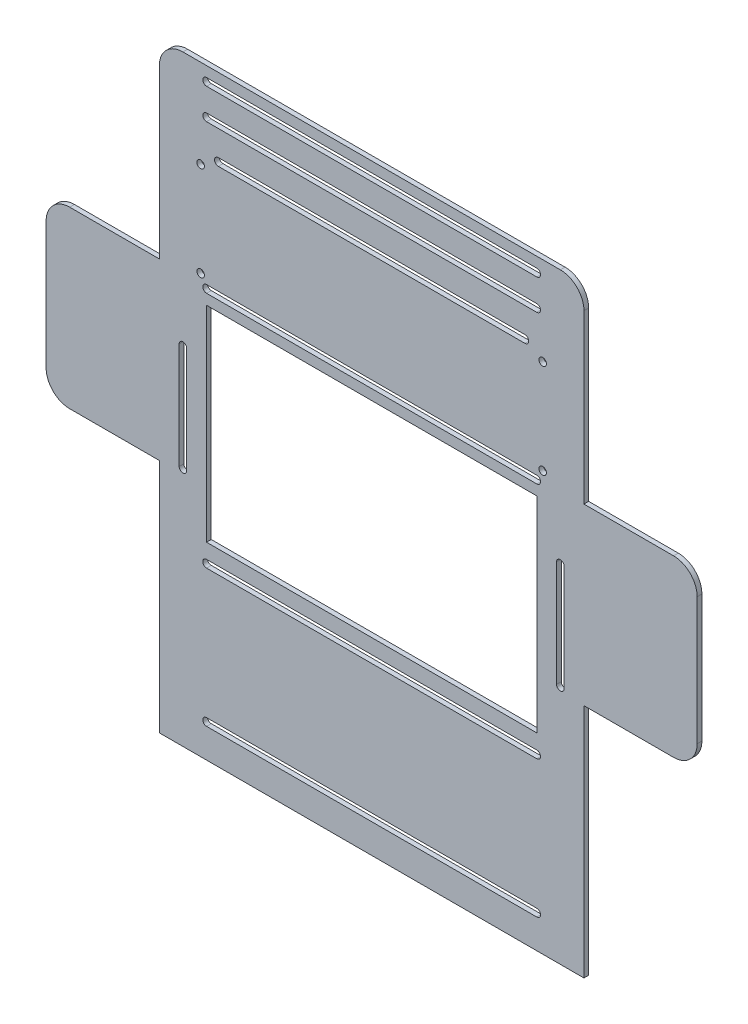
SolidWorks part; units mm, degrees
ref_plane "前视基准面" through (0, 0, 0) normal (0, 0, 1) x (1, 0, 0)
ref_plane "上视基准面" through (0, 0, 0) normal (0, 1, 0) x (1, 0, 0)
ref_plane "右视基准面" through (0, 0, 0) normal (1, 0, 0) x (0, 0, -1)
other "Configuration Table"
sketch "草图2" plane through (0, 0, 0) normal (0, 0, 1) x (1, 0, 0)
  line L0 (90, 100) -> (90, 39)
  line L1 (-90, 100) -> (90, 100)
  line L2 (-90, 100) -> (-90, 39)
  line L3 (-90, -100) -> (90, -100)
  line L5 (0, -100) -> (0, 100) construction
  line L7 (-90, 39) -> (-138, 39)
  line L9 (-90, -35) -> (-138, -35)
  line L10 (-138, 39) -> (-138, -35)
  line L15 (90, -35) -> (138, -35)
  line L16 (138, 39) -> (138, -35)
  line L17 (90, 39) -> (138, 39)
  line L18 (-90, -35) -> (-90, -100)
  line L19 (90, -35) -> (90, -100)
  point P0 (0, 0)
  dimension "D1" = 180
  dimension "D2" = 200
  dimension "D3" = 61
  dimension "D4" = 65
  dimension "D5" = 48
extrude "凸台-拉伸1" add sketch "草图2" along normal blind 2
sketch "草图3" plane through (0, 0, 2) normal (0, 0, 1) x (1, 0, 0)
  line L0 (90, -100) -> (90, -35) construction
  line L1 (-90, -100) -> (90, -100)
  line L2 (-90, -100) -> (-90, -135)
  line L3 (-90, -135) -> (90, -135)
  line L4 (90, -100) -> (90, -135)
  dimension "D1" = 35
extrude "凸台-拉伸2" add sketch "草图3" along direction (0, 0, 1) on the side against the normal up to surface (2 mm away)
sketch "草图4" plane through (0, 0, 2) normal (0, 0, 1) x (1, 0, 0)
  line L0 (90, 39) -> (90, 100) construction
  line L1 (-90, 100) -> (90, 100)
  line L2 (-90, 100) -> (-90, 120)
  line L3 (-90, 120) -> (90, 120)
  line L4 (90, 100) -> (90, 120)
  dimension "D1" = 20
extrude "凸台-拉伸3" add sketch "草图4" against normal up to surface (2 mm away) up to face at (0, -4.5, 0)
sketch "草图5" plane through (0, 0, 0) normal (0, 0, -1) x (-1, 0, 0)
  line L0 (-90, 39) -> (-90, 100) construction
  line L1 (-70, 32) -> (70, 32)
  line L2 (-70, 32) -> (-70, -55)
  line L3 (-70, -55) -> (70, -55)
  line L4 (70, 32) -> (70, -55)
  line L5 (90, 100) -> (90, 39) construction
  line L6 (90, 120) -> (-90, 120) construction
  line L7 (90, -135) -> (-90, -135) construction
  dimension "D1" = 20
  dimension "D2" = 20
  dimension "D3" = 88
  dimension "D4" = 80
extrude "切除-拉伸1" cut sketch "草图5" against normal through all
fillet "圆角1" radius 10 1 edges at (138, -35, 1)
fillet "圆角2" radius 10 1 edges at (138, 39, 1)
fillet "圆角3" radius 10 1 edges at (-138, 39, 1)
fillet "圆角4" radius 10 1 edges at (-138, -35, 1)
sketch "草图7" plane through (0, 0, 0) normal (0, 0, -1) x (-1, 0, 0)
  line L0 (-70, 114) -> (70, 114) construction
  line L1 (-70, 115.6) -> (70, 115.6)
  line L2 (-70, 112.4) -> (70, 112.4)
  line L3 (90, 120) -> (-90, 120) construction
  line L4 (-90, 39) -> (-90, 120) construction
  line L5 (90, 120) -> (90, 39) construction
  line L6 (-70, 101) -> (70, 101) construction
  line L7 (-70, 102.6) -> (70, 102.6)
  line L8 (-70, 99.4) -> (70, 99.4)
  line L9 (-70, 38) -> (70, 38) construction
  line L10 (-70, 39.6) -> (70, 39.6)
  line L11 (-70, 36.4) -> (70, 36.4)
  line L12 (70, 32) -> (-70, 32) construction
  arc A0 (-70, 115.6) -> (-70, 112.4) centre (-70, 114) ccw
  arc A1 (70, 112.4) -> (70, 115.6) centre (70, 114) ccw
  arc A2 (-70, 102.6) -> (-70, 99.4) centre (-70, 101) ccw
  arc A3 (70, 99.4) -> (70, 102.6) centre (70, 101) ccw
  arc A4 (-70, 39.6) -> (-70, 36.4) centre (-70, 38) ccw
  arc A5 (70, 36.4) -> (70, 39.6) centre (70, 38) ccw
  point P2 (0, 114)
  point P7 (0, 101)
  point P22 (0, 38)
  dimension "D1" = 6
  dimension "D2" = 3.2
  dimension "D3" = 20
  dimension "D4" = 20
  dimension "D5" = 63
  dimension "D6" = 6
  dimension "D7" = 3.2
  dimension "D8" = 3.2
  dimension "D9" = 20
  dimension "D10" = 20
  dimension "D11" = 20
  dimension "D12" = 20
extrude "切除-拉伸2" cut sketch "草图7" against normal blind 10
fillet "圆角5" radius 10 1 edges at (-90, 120, 1)
fillet "圆角6" radius 10 1 edges at (90, 120, 1)
sketch "草图10" plane through (0, 0, 0) normal (0, 0, -1) x (-1, 0, 0)
  line L0 (-70, -62.9) -> (70, -62.9) construction
  line L1 (-70, -61.3) -> (70, -61.3)
  line L2 (-70, -64.5) -> (70, -64.5)
  line L3 (-70, -121) -> (70, -121) construction
  line L4 (-70, -119.4) -> (70, -119.4)
  line L5 (-70, -122.6) -> (70, -122.6)
  line L6 (-90, -135) -> (90, -135) construction
  line L7 (-90, -135) -> (-90, -35) construction
  line L8 (90, -35) -> (90, -135) construction
  arc A0 (-70, -61.3) -> (-70, -64.5) centre (-70, -62.9) ccw
  arc A1 (70, -64.5) -> (70, -61.3) centre (70, -62.9) ccw
  arc A2 (-70, -119.4) -> (-70, -122.6) centre (-70, -121) ccw
  arc A3 (70, -122.6) -> (70, -119.4) centre (70, -121) ccw
  point P2 (0, -62.9)
  point P7 (0, -121)
  dimension "D5" = 20
  dimension "D1" = 58.1
  dimension "D2" = 14
  dimension "D3" = 3.2
  dimension "D4" = 3.2
  dimension "D6" = 20
  dimension "D7" = 20
  dimension "D8" = 20
extrude "切除-拉伸5" cut sketch "草图10" against normal blind 10
sketch "草图11" plane through (0, 0, 2) normal (0, 0, 1) x (1, 0, 0)
  line L50 (-65, 87.1) -> (65, 87.1) construction
  line L51 (-65, 88.7) -> (65, 88.7)
  line L52 (-65, 85.5) -> (65, 85.5)
  line L53 (-90, 110) -> (-90, 39) construction
  line L54 (90, 39) -> (90, 110) construction
  line L55 (-70, 36.4) -> (70, 36.4) construction
  arc A48 (-65, 88.7) -> (-65, 85.5) centre (-65, 87.1) ccw
  arc A49 (65, 85.5) -> (65, 88.7) centre (65, 87.1) ccw
  point P2 (0, 87.1)
  dimension "D1" = 25
  dimension "D2" = 25
  dimension "D3" = 49.1
  dimension "D4" = 3.2
extrude "切除-拉伸6" cut sketch "草图11" against normal through all
sketch "草图12" plane through (0, 0, 2) normal (0, 0, 1) x (1, 0, 0)
  line L0 (80, 12) -> (80, -33) construction
  line L1 (81.6, 12) -> (81.6, -33)
  line L2 (78.4, 12) -> (78.4, -33)
  line L3 (70, 32) -> (70, -55) construction
  line L4 (128, 39) -> (90, 39) construction
  line L5 (90, -35) -> (128, -35) construction
  line L6 (0, 0) -> (0, 90.7197) construction
  line L7 (-80, 12) -> (-80, -33) construction
  line L8 (-81.6, 12) -> (-81.6, -33)
  line L9 (-78.4, 12) -> (-78.4, -33)
  arc A0 (81.6, 12) -> (78.4, 12) centre (80, 12) ccw
  arc A1 (78.4, -33) -> (81.6, -33) centre (80, -33) ccw
  arc A2 (-81.6, 12) -> (-78.4, 12) centre (-80, 12) cw
  arc A3 (-78.4, -33) -> (-81.6, -33) centre (-80, -33) cw
  point P2 (80, -10.5)
  point P18 (-80, -10.5)
  dimension "D1" = 10
  dimension "D2" = 3.2
  dimension "D3" = 27
  dimension "D4" = 2
extrude "切除-拉伸7" cut sketch "草图12" against normal through all
sketch "草图13" plane through (0, 0, 2) normal (0, 0, 1) x (1, 0, 0)
  circle A0 centre (-72.5, 82.5) radius 1.6
  circle A1 centre (-72.5, 42.5) radius 1.6
  circle A2 centre (72.5, 82.5) radius 1.6
  circle A3 centre (72.5, 42.5) radius 1.6
extrude "切除-拉伸8" cut sketch "草图13" against normal blind 10
sketch "草图14" plane through (0, 0, 0) normal (0, 0, -1) x (-1, 0, 0)
  line L0 (-54.7377, 100.9977) -> (-32.9256, 114.0127)
  line L2 (-32.9256, 114.0127) -> (-32.9256, 80.4181)
  dimension "D1" = 25.4
